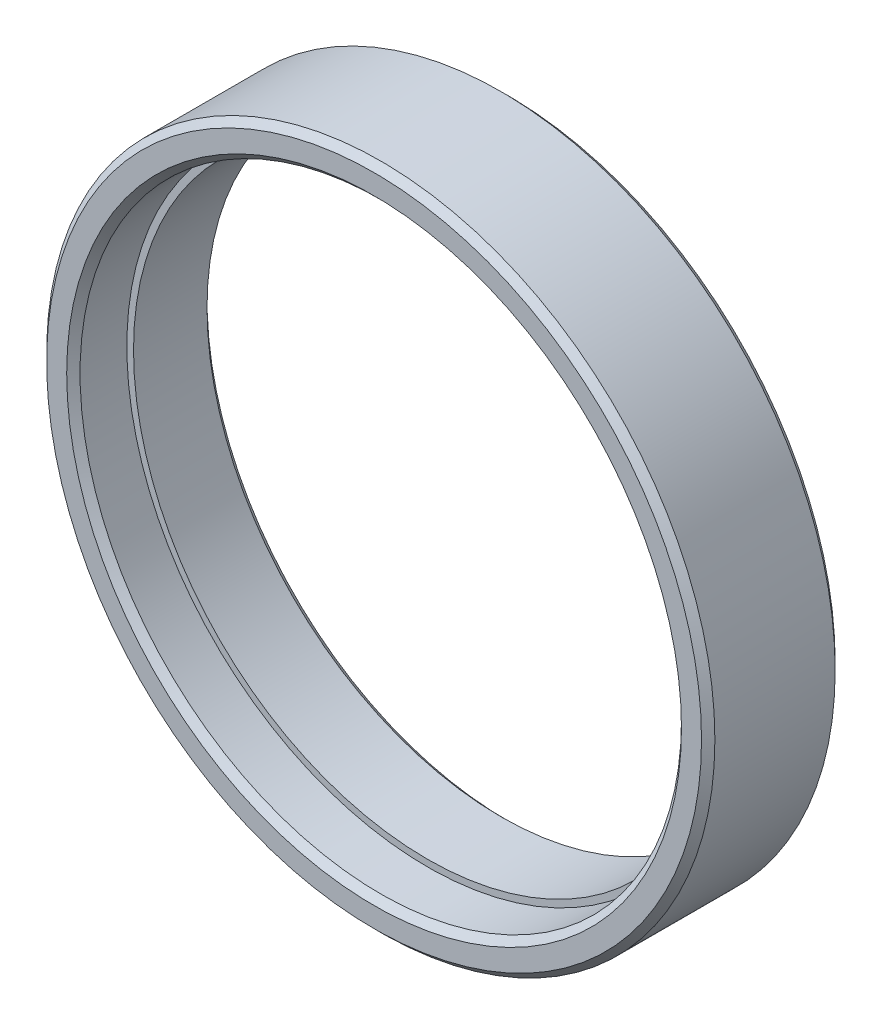
SolidWorks part; units mm, degrees
ref_plane "정면" through (0, 0, 0) normal (0, 0, 1) x (1, 0, 0)
ref_plane "윗면" through (0, 0, 0) normal (0, 1, 0) x (1, 0, 0)
ref_plane "우측면" through (0, 0, 0) normal (1, 0, 0) x (0, 0, -1)
sketch "스케치1" plane through (0, 0, 0) normal (0, 0, 1) x (1, 0, 0)
  circle A0 centre (0, 0) radius 50
  dimension "D1" = 100
extrude "보스-돌출1" add sketch "스케치1" along normal blind 20 contours A0
sketch "스케치2" plane through (0, 0, 20) normal (0, 0, 1) x (1, 0, 0)
  circle A0 centre (0, 0) radius 45
  dimension "D1" = 90
extrude "컷-돌출1" cut sketch "스케치2" against normal blind 8 contours A0
sketch "스케치3" plane through (0, 0, 0) normal (0, 0, -1) x (-1, 0, 0)
  circle A0 centre (0, 0) radius 44
  dimension "D1" = 88
extrude "컷-돌출2" cut sketch "스케치3" against normal blind 12 contours A0
chamfer "모따기1" distance 1 angle 45 4 edges at (-44, 0, 0) (50, 0, 0) (50, 0, 20) (45, 0, 20)
